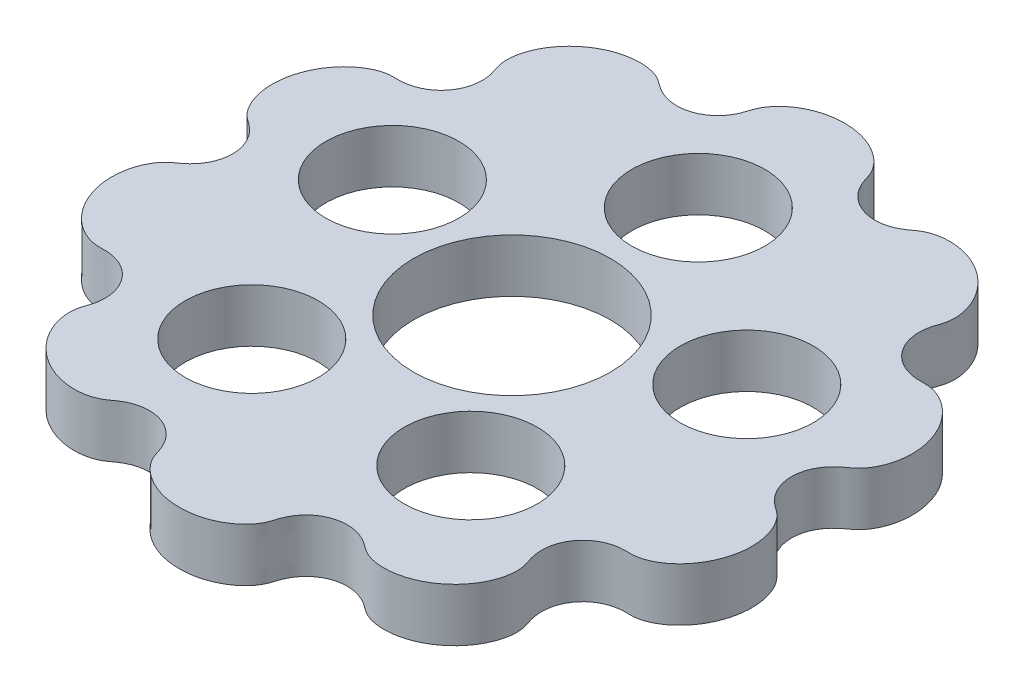
SolidWorks part; units mm, degrees
ref_plane "Front Plane" through (0, 0, 0) normal (0, 0, 1) x (1, 0, 0)
ref_plane "Top Plane" through (0, 0, 0) normal (0, 1, 0) x (1, 0, 0)
ref_plane "Right Plane" through (0, 0, 0) normal (1, 0, 0) x (0, 0, -1)
sketch "Sketch1" plane through (0, 0, 0) normal (0, 1, 0) x (1, 0, 0)
  line L0 (52.5001, 0.0415) -> (52.5, 0)
  spline S0 degree 4 poles (50.5137, 27.6197) (50.9839, 27.5812) (51.8522, 27.4156) (53.4265, 26.845) (55.5206, 25.4783) (57.5342, 23.3814) (59.2047, 20.4519) (60.0271, 17.5454) (60.2034, 14.9243) (59.9788, 12.88) (59.6275, 11.4276) (59.1883, 10.2668) (58.7445, 9.3842) (58.2852, 8.6575) (57.8967, 8.1479) (57.5285, 7.7404) (57.208, 7.4353) (56.9519, 7.2176) (56.636, 6.976) (56.3222, 6.7567) (56.0097, 6.5358) (55.6427, 6.2595) (55.2623, 5.9506) (54.8217, 5.547) (54.3431, 5.0304) (53.8948, 4.4489) (53.5024, 3.829) (53.1698, 3.1757) (52.9427, 2.6012) (52.7935, 2.1219) (52.6991, 1.7471) (52.6422, 1.4822) (52.5946, 1.2148) (52.5565, 0.9474) (52.5279, 0.6739) (52.5088, 0.4201) (52.4999, 0.1167) (52.4991, -0.0504) (52.5043, -0.2752) (52.5136, -0.4749) (52.531, -0.7089) (52.5611, -0.9887) (52.6094, -1.3156) (52.6824, -1.6816) (52.7948, -2.1324) (53.0174, -2.8309) (53.4278, -3.7531) (54.0707, -4.7446) (54.8301, -5.5754) (55.5037, -6.157) (56.0124, -6.539) (56.4108, -6.818) (56.7924, -7.0894) (57.142, -7.3728) (57.5207, -7.7299) (57.9157, -8.1698) (58.4933, -8.9376) (59.0883, -9.9991) (59.6003, -11.3023) (60.0493, -13.197) (60.2144, -15.3932) (59.9369, -17.9726) (59.1239, -20.4456) (58.0615, -22.4161) (56.9372, -23.9185) (55.905, -25.0086) (54.6695, -26.0286) (53.2974, -26.8599) (52.0381, -27.3608) (50.9617, -27.59) (50.2174, -27.6452) (49.7229, -27.6436) (49.2436, -27.6335) (48.779, -27.6384) (48.2213, -27.6667) (47.4128, -27.7584) (46.3618, -27.9976) (45.1066, -28.5075) (43.8309, -29.342) (42.7421, -30.4104) (41.8865, -31.6717) (41.3014, -33.0572) (40.9958, -34.5041) (40.9663, -35.8518) (41.1191, -36.9419) (41.3328, -37.7752) (41.5169, -38.3484) (41.6666, -38.779) (41.8007, -39.1927) (41.9033, -39.5936) (41.9931, -40.0789) (42.0522, -40.6496) (42.0653, -41.3702) (41.996, -42.235) (41.8118, -43.2683) (41.4633, -44.4497) (40.7951, -46.0262) (39.6316, -47.8911) (37.8812, -49.8104) (35.7571, -51.3288) (33.7228, -52.2936) (31.9095, -52.8411) (30.4175, -53.1066) (28.8666, -53.1869) (27.5064, -53.0662) (26.3596, -52.8062) (25.4812, -52.4838) (24.9495, -52.2275) (24.5453, -51.9879) (24.1978, -51.7525) (23.9172, -51.5436) (23.6381, -51.3332) (23.232, -51.041) (22.7473, -50.7202) (21.9663, -50.2822) (20.8507, -49.8374) (19.5115, -49.545) (17.9731, -49.5159) (16.4648, -49.7896) (15.0488, -50.3537) (13.7947, -51.1659) (12.7367, -52.1794) (11.9586, -53.2621) (11.4706, -54.2355) (11.1728, -55.0336) (10.9942, -55.6012) (10.863, -56.033) (10.7199, -56.4397) (10.5576, -56.817) (10.3352, -57.2528) (10.0392, -57.7376) (9.6188, -58.3143) (9.0494, -58.9575) (8.026, -59.9148) (6.4149, -61.014) (4.1854, -61.9905) (1.3392, -62.5603) (-1.5555, -62.5373) (-4.0271, -62.0021) (-6.0205, -61.178) (-7.4336, -60.3182) (-8.3498, -59.6134) (-9.0591, -58.943) (-9.5889, -58.3483) (-10.0398, -57.7416) (-10.3653, -57.2066) (-10.602, -56.7252) (-10.7847, -56.2661) (-10.9036, -55.901) (-11.0089, -55.5537) (-11.134, -55.1628) (-11.2692, -54.775) (-11.524, -54.1353) (-11.9704, -53.2592) (-12.6641, -52.2657) (-13.6882, -51.2531) (-14.8984, -50.4381) (-16.2819, -49.8468) (-17.79, -49.53) (-19.3539, -49.5225) (-20.902, -49.8356) (-22.1148, -50.342) (-22.9585, -50.8486) (-23.5039, -51.2352) (-23.8505, -51.4923) (-24.1373, -51.7091) (-24.4322, -51.9153) (-24.8449, -52.1675) (-25.3219, -52.4127) (-25.9648, -52.6717) (-26.7816, -52.9052) (-27.8082, -53.0938) (-29.0445, -53.179) (-30.4446, -53.106) (-31.9828, -52.8257) (-33.8493, -52.2469) (-35.9581, -51.2161) (-37.8451, -49.8114) (-39.4342, -48.0894) (-40.5175, -46.4752) (-41.2219, -45.0883) (-41.6768, -43.8047) (-41.9333, -42.6668) (-42.0454, -41.7024) (-42.0674, -40.926) (-42.0211, -40.2648) (-41.9322, -39.7238) (-41.8104, -39.2249) (-41.689, -38.8442) (-41.5576, -38.4672) (-41.4084, -38.0119) (-41.2638, -37.5172) (-41.1226, -36.9013) (-41.0183, -36.1616) (-40.9838, -35.3806) (-41.0358, -34.4173) (-41.2507, -33.2654) (-41.725, -31.9746) (-42.561, -30.6268) (-43.6662, -29.4706) (-44.9678, -28.5757) (-46.4068, -27.9666) (-47.6784, -27.6986) (-48.7214, -27.6297) (-49.4554, -27.6377) (-49.8839, -27.6454) (-50.3123, -27.6377) (-50.9842, -27.5865) (-52.0202, -27.3671) (-53.2997, -26.8583) (-54.684, -26.0188) (-55.9292, -24.9892) (-56.989, -23.8601) (-58.1366, -22.3017) (-59.199, -20.2738) (-59.9869, -17.7487) (-60.2196, -15.1335) (-60.0091, -12.9319) (-59.532, -11.1058) (-59.0205, -9.8698) (-58.4445, -8.8705) (-57.9119, -8.1659) (-57.5339, -7.7452) (-57.186, -7.4139) (-56.8826, -7.1604) (-56.5405, -6.9081) (-56.167, -6.6487) (-55.6705, -6.2883) (-54.9929, -5.7308) (-54.2103, -4.9216) (-53.4318, -3.7935) (-52.83, -2.4288) (-52.5002, -0.9669) (-52.4571, 0.5522) (-52.7153, 2.061) (-53.2627, 3.4832) (-54.0035, 4.6556) (-54.7388, 5.4802) (-55.3636, 6.0389) (-55.8227, 6.3989) (-56.1997, 6.6716) (-56.5809, 6.9362) (-56.9524, 7.213) (-57.357, 7.5655) (-57.779, 8.0056) (-58.333, 8.7033) (-58.9309, 9.69) (-59.4684, 10.9205) (-59.881, 12.3939) (-60.1041, 13.8869) (-60.1629, 15.7726) (-59.8944, 18.0319) (-59.2221, 20.2152) (-58.1717, 22.2394) (-57.0556, 23.7771) (-56.0256, 24.8955) (-54.8008, 25.934) (-53.5992, 26.6866) (-52.4791, 27.1881) (-51.5414, 27.4638) (-50.908, 27.5862) (-50.3231, 27.6424) (-49.7934, 27.6455) (-49.1614, 27.6309) (-48.4256, 27.6439) (-47.4521, 27.7432) (-46.2534, 28.0311) (-44.967, 28.579) (-43.6819, 29.4595) (-42.5816, 30.6012) (-41.7415, 31.9406) (-41.2602, 33.2313) (-41.0399, 34.3848) (-40.9839, 35.3498) (-41.0156, 36.1324) (-41.1174, 36.8734) (-41.2569, 37.4904) (-41.4004, 37.9861) (-41.549, 38.442) (-41.6805, 38.8194) (-41.8032, 39.2) (-41.9273, 39.699) (-42.0184, 40.2402) (-42.0669, 40.9021) (-42.0471, 41.6796) (-41.9591, 42.4524) (-41.8098, 43.2156) (-41.553, 44.1531) (-41.1412, 45.2456) (-40.5256, 46.4617) (-39.4424, 48.0795) (-37.854, 49.8036) (-35.9683, 51.2097) (-33.8615, 52.2416) (-31.9987, 52.8217) (-30.4634, 53.1036) (-28.8372, 53.1913) (-27.4076, 53.0564) (-26.2012, 52.7644) (-25.2794, 52.3967) (-24.6778, 52.0804) (-24.2175, 51.7696) (-23.874, 51.5099) (-23.5282, 51.253) (-22.9846, 50.8655) (-22.1441, 50.3567) (-20.9354, 49.8462) (-19.3913, 49.5265) (-17.8293, 49.5261) (-16.3197, 49.835) (-14.9321, 50.4197) (-13.7159, 51.2302) (-12.6861, 52.2396) (-11.9875, 53.2313) (-11.5372, 54.1066) (-11.2802, 54.7459) (-11.1435, 55.1346) (-11.0173, 55.5266) (-10.9116, 55.8747) (-10.7936, 56.2409) (-10.6126, 56.7015) (-10.3777, 57.1843) (-10.0537, 57.7211) (-9.604, 58.33) (-9.0747, 58.927) (-8.3659, 59.5999) (-7.4495, 60.3076) (-6.0356, 61.1707) (-4.0402, 61.9984) (-1.5791, 62.5336) (1.2918, 62.5618) (3.7523, 62.0799) (5.746, 61.3079) (7.1998, 60.4742) (8.1838, 59.7553) (9.0853, 58.9347) (9.773, 58.1413) (10.2664, 57.4013) (10.5906, 56.7517) (10.783, 56.2729) (10.9298, 55.8188) (11.0821, 55.3106) (11.2729, 54.758) (11.5071, 54.1882) (11.7952, 53.6084) (12.2337, 52.8793) (12.8842, 52.0381) (13.7961, 51.1677) (15.0329, 50.3633) (16.4413, 49.7961) (17.9467, 49.5176) (19.4906, 49.5425) (20.9881, 49.8658) (22.167, 50.3685) (23.0025, 50.8774) (23.5419, 51.263) (23.8838, 51.5174) (24.2239, 51.7741) (24.6778, 52.0798) (25.2689, 52.3913) (26.1721, 52.7541) (27.3524, 53.0458) (28.7524, 53.1873) (30.3468, 53.1154) (31.8542, 52.855) (33.6865, 52.3092) (35.7348, 51.3434) (37.8679, 49.8229) (39.6227, 47.9021) (40.7867, 46.0415) (41.4564, 44.4684) (41.8066, 43.2894) (41.9928, 42.2582) (42.0643, 41.3949) (42.0536, 40.6755) (41.9967, 40.1055) (41.9092, 39.6204) (41.8084, 39.2195) (41.676, 38.8059) (41.5263, 38.3761) (41.3414, 37.8045) (41.1252, 36.9734) (40.9684, 35.8858) (40.9919, 34.5404) (41.2901, 33.0941) (41.8697, 31.7015) (42.7272, 30.4257) (43.8268, 29.3427) (45.1246, 28.4959) (46.3067, 28.0217) (47.2768, 27.7899) (48.0092, 27.6897) (48.4792, 27.6507) (48.9504, 27.6345) (49.4215, 27.6363) (49.8923, 27.6467) (50.3633, 27.638) (50.9053, 27.5853) (51.5125, 27.4703) (52.3773, 27.2213) (53.4476, 26.7608) (54.6115, 26.0642) (56.1125, 24.854) (57.6371, 23.1341) (58.9891, 20.8488) (59.9328, 17.9964) (60.2137, 15.4073) (60.0515, 13.2142) (59.6063, 11.3218) (59.0976, 10.0195) (58.506, 8.9581) (57.9317, 8.1896) (57.539, 7.749) (57.1625, 7.3909) (56.8149, 7.1065) (56.4347, 6.8345) (56.0365, 6.5563) (55.5274, 6.176) (54.8528, 5.5976) (54.2148, 4.9051) (53.6468, 4.092) (53.2635, 3.3667) (53.0462, 2.8643) (52.8911, 2.4331) (52.7829, 2.0805) (52.6912, 1.7204) (52.6165, 1.3555) (52.5665, 1.0291) (52.5349, 0.7496) (52.5162, 0.516) (52.5059, 0.3168) (52.4995, 0.0913) (52.4994, -0.0498) (52.5037, -0.2593) (52.5117, -0.4351) (52.5205, -0.5703) (52.5346, -0.7372) (52.5633, -1.0062) (52.6182, -1.3763) (52.7261, -1.8914) (52.9083, -2.5128) (53.1636, -3.1635) (53.5039, -3.8331) (53.9066, -4.4669) (54.3673, -5.0599) (54.8485, -5.5734) (55.3344, -6.0144) (55.8114, -6.3927) (56.2105, -6.6789) (56.5558, -6.9194) (56.8563, -7.1425) (57.1104, -7.3492) (57.439, -7.6488) (57.8233, -8.059) (58.2283, -8.5752) (58.7047, -9.312) (59.1632, -10.2073) (59.5635, -11.2492) (59.8752, -12.434) (60.1105, -13.9192) (60.1782, -15.9789) (59.8062, -18.5974) (58.6629, -21.6162) (56.9432, -24.0677) (55.1186, -25.7376) (53.5134, -26.7273) (52.3156, -27.2564) (51.3998, -27.5063) (50.8196, -27.5938) (50.5276, -27.6185) knots 0 0 0 0 0 0.003711 0.006927 0.013093 0.019514 0.026363 0.033214 0.036638 0.040062 0.042505 0.044948 0.046387 0.047827 0.049266 0.049986 0.050706 0.051309 0.051911 0.053117 0.053719 0.054322 0.055527 0.056973 0.058419 0.05986 0.0613 0.062741 0.064183 0.064716 0.06525 0.065783 0.066317 0.06685 0.067384 0.067918 0.068451 0.068823 0.069195 0.069567 0.069939 0.070683 0.071427 0.072155 0.072882 0.074337 0.077196 0.080074 0.082134 0.083164 0.084195 0.08508 0.085965 0.08685 0.087735 0.089174 0.090614 0.094403 0.097279 0.100155 0.105904 0.111655 0.117552 0.1205 0.123448 0.126397 0.129346 0.133079 0.136028 0.137001 0.137974 0.138947 0.13992 0.140776 0.141631 0.143342 0.146321 0.149231 0.152234 0.155269 0.158252 0.161152 0.164002 0.166843 0.168806 0.169787 0.170769 0.171582 0.172396 0.17321 0.174024 0.175466 0.176908 0.178876 0.180844 0.183715 0.186585 0.192323 0.198063 0.204015 0.206991 0.209967 0.212943 0.215919 0.219183 0.220677 0.222171 0.223273 0.223823 0.224374 0.225475 0.226025 0.226576 0.228312 0.230048 0.233064 0.235996 0.239038 0.242085 0.245052 0.247918 0.250729 0.253554 0.255493 0.256462 0.257431 0.258238 0.259046 0.259854 0.260662 0.262088 0.263514 0.265465 0.267416 0.273101 0.278785 0.28447 0.290104 0.295736 0.298553 0.30137 0.303095 0.30482 0.306227 0.307634 0.309039 0.309742 0.310445 0.311522 0.312061 0.312599 0.313677 0.314754 0.317479 0.320324 0.323167 0.326029 0.328899 0.332099 0.335219 0.338253 0.341251 0.342384 0.34295 0.343516 0.344649 0.345215 0.345781 0.347323 0.348865 0.350662 0.352459 0.355528 0.358598 0.361668 0.364738 0.370878 0.376986 0.38004 0.383094 0.386148 0.389202 0.390729 0.392257 0.393783 0.395309 0.395938 0.396567 0.397824 0.398453 0.399082 0.400339 0.401881 0.403423 0.404954 0.406485 0.409464 0.412615 0.415708 0.418884 0.421967 0.424963 0.427932 0.429056 0.43018 0.430743 0.431305 0.432429 0.43548 0.439041 0.442082 0.445123 0.448164 0.451204 0.457286 0.46306 0.468832 0.47172 0.474607 0.47788 0.479326 0.480773 0.48155 0.482328 0.483106 0.483883 0.484896 0.485909 0.487935 0.490785 0.493727 0.496638 0.499606 0.502511 0.505617 0.508611 0.511524 0.513364 0.514284 0.515204 0.516115 0.517026 0.517938 0.518849 0.520335 0.521821 0.52494 0.527905 0.530869 0.533833 0.536797 0.542726 0.548698 0.551683 0.554667 0.557654 0.56064 0.564291 0.565785 0.56728 0.568321 0.569363 0.570405 0.571447 0.5733 0.575153 0.578095 0.581117 0.58424 0.587334 0.590492 0.593476 0.595011 0.596546 0.59809 0.599633 0.600892 0.601521 0.602151 0.603409 0.604039 0.604668 0.606196 0.607725 0.609254 0.610783 0.612313 0.613842 0.6169 0.619959 0.623017 0.629134 0.635265 0.63833 0.641395 0.644459 0.647524 0.651113 0.652653 0.654193 0.655323 0.656453 0.657019 0.657584 0.658714 0.661709 0.664737 0.667852 0.671048 0.673919 0.676788 0.679636 0.682487 0.685207 0.686288 0.687369 0.687909 0.68845 0.68953 0.690234 0.690937 0.692343 0.693753 0.695162 0.696889 0.698617 0.701438 0.70426 0.7099 0.715542 0.721126 0.72671 0.729502 0.732295 0.73429 0.736286 0.739084 0.740539 0.741266 0.741994 0.743144 0.744294 0.745444 0.746594 0.74799 0.749386 0.752135 0.754942 0.757861 0.760934 0.764011 0.766914 0.769939 0.772922 0.774041 0.7746 0.775159 0.776277 0.777396 0.778902 0.780409 0.783927 0.786931 0.789935 0.792938 0.795942 0.801949 0.80768 0.813409 0.816275 0.819141 0.821107 0.823072 0.824512 0.825951 0.826764 0.827577 0.82839 0.829203 0.830182 0.831161 0.833118 0.835958 0.838802 0.841696 0.844677 0.847761 0.850824 0.853764 0.856799 0.857727 0.858655 0.859582 0.86051 0.861437 0.862364 0.86329 0.864217 0.86572 0.867222 0.870363 0.873362 0.876361 0.882358 0.888357 0.894099 0.89984 0.902711 0.905583 0.909366 0.910804 0.912242 0.913125 0.914008 0.914891 0.915774 0.916804 0.917834 0.919893 0.922762 0.924189 0.925616 0.926343 0.927069 0.927795 0.928521 0.929264 0.930008 0.930379 0.930751 0.931123 0.931494 0.932028 0.932295 0.932562 0.932829 0.933096 0.93363 0.934697 0.935765 0.937242 0.938718 0.940194 0.941669 0.943146 0.944622 0.945727 0.946831 0.947936 0.948488 0.949041 0.949777 0.950514 0.951987 0.953461 0.954935 0.957413 0.959892 0.962228 0.964563 0.969234 0.976064 0.982895 0.989723 0.992556 0.995389 0.997695 1 1 1 1 1 construction
  spline S1 degree 4 poles (52.5, 0) (52.5, -0.0408) (52.5008, -0.1231) (52.5043, -0.2752) (52.5136, -0.4749) (52.531, -0.7089) (52.5611, -0.9887) (52.6094, -1.3156) (52.6824, -1.6816) (52.7948, -2.1324) (53.0174, -2.8309) (53.4278, -3.7531) (54.0707, -4.7446) (54.8301, -5.5754) (55.5037, -6.157) (56.0124, -6.539) (56.4108, -6.818) (56.7924, -7.0894) (57.142, -7.3728) (57.5207, -7.7299) (57.9157, -8.1698) (58.4933, -8.9376) (59.0883, -9.9991) (59.6003, -11.3023) (60.0493, -13.197) (60.2144, -15.3932) (59.9369, -17.9726) (59.1239, -20.4456) (58.0615, -22.4161) (56.9372, -23.9185) (55.905, -25.0086) (54.6695, -26.0286) (53.2974, -26.8599) (52.0381, -27.3608) (50.9617, -27.59) (50.2174, -27.6452) (49.7229, -27.6436) (49.2436, -27.6335) (48.779, -27.6384) (48.2213, -27.6667) (47.4128, -27.7584) (46.3618, -27.9976) (45.1066, -28.5075) (43.8309, -29.342) (42.7421, -30.4104) (41.8865, -31.6717) (41.3014, -33.0572) (40.9958, -34.5041) (40.9663, -35.8518) (41.1191, -36.9419) (41.3328, -37.7752) (41.5169, -38.3484) (41.6666, -38.779) (41.8007, -39.1927) (41.9033, -39.5936) (41.9931, -40.0789) (42.0522, -40.6496) (42.0653, -41.3702) (41.996, -42.235) (41.8118, -43.2683) (41.4633, -44.4497) (40.7951, -46.0262) (39.6316, -47.8911) (37.8812, -49.8104) (35.7571, -51.3288) (33.7228, -52.2936) (31.9095, -52.8411) (30.4175, -53.1066) (28.8666, -53.1869) (27.5064, -53.0662) (26.3596, -52.8062) (25.4812, -52.4838) (24.9495, -52.2275) (24.5453, -51.9879) (24.1978, -51.7525) (23.9172, -51.5436) (23.6381, -51.3332) (23.232, -51.041) (22.7473, -50.7202) (21.9663, -50.2822) (20.8507, -49.8374) (19.5115, -49.545) (17.9731, -49.5159) (16.4648, -49.7896) (15.0488, -50.3537) (13.7947, -51.1659) (12.7367, -52.1794) (11.9586, -53.2621) (11.4706, -54.2355) (11.1728, -55.0336) (10.9942, -55.6012) (10.863, -56.033) (10.7199, -56.4397) (10.5576, -56.817) (10.3352, -57.2528) (10.0392, -57.7376) (9.6188, -58.3143) (9.0494, -58.9575) (8.026, -59.9148) (6.4149, -61.014) (4.1854, -61.9905) (1.3392, -62.5603) (-1.5555, -62.5373) (-4.0271, -62.0021) (-6.0205, -61.178) (-7.4336, -60.3182) (-8.3498, -59.6134) (-9.0591, -58.943) (-9.5889, -58.3483) (-10.0398, -57.7416) (-10.3653, -57.2066) (-10.602, -56.7252) (-10.7847, -56.2661) (-10.9036, -55.901) (-11.0089, -55.5537) (-11.134, -55.1628) (-11.2692, -54.775) (-11.524, -54.1353) (-11.9704, -53.2592) (-12.6641, -52.2657) (-13.6882, -51.2531) (-14.8984, -50.4381) (-16.2819, -49.8468) (-17.79, -49.53) (-19.3539, -49.5225) (-20.902, -49.8356) (-22.1148, -50.342) (-22.9585, -50.8486) (-23.5039, -51.2352) (-23.8505, -51.4923) (-24.1373, -51.7091) (-24.4322, -51.9153) (-24.8449, -52.1675) (-25.3219, -52.4127) (-25.9648, -52.6717) (-26.7816, -52.9052) (-27.8082, -53.0938) (-29.0445, -53.179) (-30.4446, -53.106) (-31.9828, -52.8257) (-33.8493, -52.2469) (-35.9581, -51.2161) (-37.8451, -49.8114) (-39.4342, -48.0894) (-40.5175, -46.4752) (-41.2219, -45.0883) (-41.6768, -43.8047) (-41.9333, -42.6668) (-42.0454, -41.7024) (-42.0674, -40.926) (-42.0211, -40.2648) (-41.9322, -39.7238) (-41.8104, -39.2249) (-41.689, -38.8442) (-41.5576, -38.4672) (-41.4084, -38.0119) (-41.2638, -37.5172) (-41.1226, -36.9013) (-41.0183, -36.1616) (-40.9838, -35.3806) (-41.0358, -34.4173) (-41.2507, -33.2654) (-41.725, -31.9746) (-42.561, -30.6268) (-43.6662, -29.4706) (-44.9678, -28.5757) (-46.4068, -27.9666) (-47.6784, -27.6986) (-48.7214, -27.6297) (-49.4554, -27.6377) (-49.8839, -27.6454) (-50.3123, -27.6377) (-50.9842, -27.5865) (-52.0202, -27.3671) (-53.2997, -26.8583) (-54.684, -26.0188) (-55.9292, -24.9892) (-56.989, -23.8601) (-58.1366, -22.3017) (-59.199, -20.2738) (-59.9869, -17.7487) (-60.2196, -15.1335) (-60.0091, -12.9319) (-59.532, -11.1058) (-59.0205, -9.8698) (-58.4445, -8.8705) (-57.9119, -8.1659) (-57.5339, -7.7452) (-57.186, -7.4139) (-56.8826, -7.1604) (-56.5405, -6.9081) (-56.167, -6.6487) (-55.6705, -6.2883) (-54.9929, -5.7308) (-54.2103, -4.9216) (-53.4318, -3.7935) (-52.83, -2.4288) (-52.5002, -0.9669) (-52.4571, 0.5522) (-52.7153, 2.061) (-53.2627, 3.4832) (-54.0035, 4.6556) (-54.7388, 5.4802) (-55.3636, 6.0389) (-55.8227, 6.3989) (-56.1997, 6.6716) (-56.5809, 6.9362) (-56.9524, 7.213) (-57.357, 7.5655) (-57.779, 8.0056) (-58.333, 8.7033) (-58.9309, 9.69) (-59.4684, 10.9205) (-59.881, 12.3939) (-60.1041, 13.8869) (-60.1629, 15.7726) (-59.8944, 18.0319) (-59.2221, 20.2152) (-58.1717, 22.2394) (-57.0556, 23.7771) (-56.0256, 24.8955) (-54.8008, 25.934) (-53.5992, 26.6866) (-52.4791, 27.1881) (-51.5414, 27.4638) (-50.908, 27.5862) (-50.3231, 27.6424) (-49.7934, 27.6455) (-49.1614, 27.6309) (-48.4256, 27.6439) (-47.4521, 27.7432) (-46.2534, 28.0311) (-44.967, 28.579) (-43.6819, 29.4595) (-42.5816, 30.6012) (-41.7415, 31.9406) (-41.2602, 33.2313) (-41.0399, 34.3848) (-40.9839, 35.3498) (-41.0156, 36.1324) (-41.1174, 36.8734) (-41.2569, 37.4904) (-41.4004, 37.9861) (-41.549, 38.442) (-41.6805, 38.8194) (-41.8032, 39.2) (-41.9273, 39.699) (-42.0184, 40.2402) (-42.0669, 40.9021) (-42.0471, 41.6796) (-41.9591, 42.4524) (-41.8098, 43.2156) (-41.553, 44.1531) (-41.1412, 45.2456) (-40.5256, 46.4617) (-39.4424, 48.0795) (-37.854, 49.8036) (-35.9683, 51.2097) (-33.8615, 52.2416) (-31.9987, 52.8217) (-30.4634, 53.1036) (-28.8372, 53.1913) (-27.4076, 53.0564) (-26.2012, 52.7644) (-25.2794, 52.3967) (-24.6778, 52.0804) (-24.2175, 51.7696) (-23.874, 51.5099) (-23.5282, 51.253) (-22.9846, 50.8655) (-22.1441, 50.3567) (-20.9354, 49.8462) (-19.3913, 49.5265) (-17.8293, 49.5261) (-16.3197, 49.835) (-14.9321, 50.4197) (-13.7159, 51.2302) (-12.6861, 52.2396) (-11.9875, 53.2313) (-11.5372, 54.1066) (-11.2802, 54.7459) (-11.1435, 55.1346) (-11.0173, 55.5266) (-10.9116, 55.8747) (-10.7936, 56.2409) (-10.6126, 56.7015) (-10.3777, 57.1843) (-10.0537, 57.7211) (-9.604, 58.33) (-9.0747, 58.927) (-8.3659, 59.5999) (-7.4495, 60.3076) (-6.0356, 61.1707) (-4.0402, 61.9984) (-1.5791, 62.5336) (1.2918, 62.5618) (3.7523, 62.0799) (5.746, 61.3079) (7.1998, 60.4742) (8.1838, 59.7553) (9.0853, 58.9347) (9.773, 58.1413) (10.2664, 57.4013) (10.5906, 56.7517) (10.783, 56.2729) (10.9298, 55.8188) (11.0821, 55.3106) (11.2729, 54.758) (11.5071, 54.1882) (11.7952, 53.6084) (12.2337, 52.8793) (12.8842, 52.0381) (13.7961, 51.1677) (15.0329, 50.3633) (16.4413, 49.7961) (17.9467, 49.5176) (19.4906, 49.5425) (20.9881, 49.8658) (22.167, 50.3685) (23.0025, 50.8774) (23.5419, 51.263) (23.8838, 51.5174) (24.2239, 51.7741) (24.6778, 52.0798) (25.2689, 52.3913) (26.1721, 52.7541) (27.3524, 53.0458) (28.7524, 53.1873) (30.3468, 53.1154) (31.8542, 52.855) (33.6865, 52.3092) (35.7348, 51.3434) (37.8679, 49.8229) (39.6227, 47.9021) (40.7867, 46.0415) (41.4564, 44.4684) (41.8066, 43.2894) (41.9928, 42.2582) (42.0643, 41.3949) (42.0536, 40.6755) (41.9967, 40.1055) (41.9092, 39.6204) (41.8084, 39.2195) (41.676, 38.8059) (41.5263, 38.3761) (41.3414, 37.8045) (41.1252, 36.9734) (40.9684, 35.8858) (40.9919, 34.5404) (41.2901, 33.0941) (41.8697, 31.7015) (42.7272, 30.4257) (43.8268, 29.3427) (45.1246, 28.4959) (46.3067, 28.0217) (47.2768, 27.7899) (48.0092, 27.6897) (48.4792, 27.6507) (48.9504, 27.6345) (49.4215, 27.6363) (49.8923, 27.6467) (50.3633, 27.638) (50.9053, 27.5853) (51.5125, 27.4703) (52.3773, 27.2213) (53.4476, 26.7608) (54.6115, 26.0642) (56.1125, 24.854) (57.6371, 23.1341) (58.9891, 20.8488) (59.9328, 17.9964) (60.2137, 15.4073) (60.0515, 13.2142) (59.6063, 11.3218) (59.0976, 10.0195) (58.506, 8.9581) (57.9317, 8.1896) (57.539, 7.749) (57.1625, 7.3909) (56.8149, 7.1065) (56.4347, 6.8345) (56.0365, 6.5563) (55.5274, 6.176) (54.8528, 5.5976) (54.2148, 4.9051) (53.6468, 4.092) (53.2635, 3.3667) (53.0462, 2.8643) (52.8911, 2.4331) (52.7829, 2.0805) (52.6912, 1.7204) (52.6165, 1.3555) (52.5665, 1.0291) (52.5349, 0.7496) (52.5162, 0.516) (52.5059, 0.3168) (52.5015, 0.1643) (52.5003, 0.0822) (52.5001, 0.0415) knots 0.068451 0.068451 0.068451 0.068451 0.068451 0.068823 0.069195 0.069567 0.069939 0.070683 0.071427 0.072155 0.072882 0.074337 0.077196 0.080074 0.082134 0.083164 0.084195 0.08508 0.085965 0.08685 0.087735 0.089174 0.090614 0.094403 0.097279 0.100155 0.105904 0.111655 0.117552 0.1205 0.123448 0.126397 0.129346 0.133079 0.136028 0.137001 0.137974 0.138947 0.13992 0.140776 0.141631 0.143342 0.146321 0.149231 0.152234 0.155269 0.158252 0.161152 0.164002 0.166843 0.168806 0.169787 0.170769 0.171582 0.172396 0.17321 0.174024 0.175466 0.176908 0.178876 0.180844 0.183715 0.186585 0.192323 0.198063 0.204015 0.206991 0.209967 0.212943 0.215919 0.219183 0.220677 0.222171 0.223273 0.223823 0.224374 0.225475 0.226025 0.226576 0.228312 0.230048 0.233064 0.235996 0.239038 0.242085 0.245052 0.247918 0.250729 0.253554 0.255493 0.256462 0.257431 0.258238 0.259046 0.259854 0.260662 0.262088 0.263514 0.265465 0.267416 0.273101 0.278785 0.28447 0.290104 0.295736 0.298553 0.30137 0.303095 0.30482 0.306227 0.307634 0.309039 0.309742 0.310445 0.311522 0.312061 0.312599 0.313677 0.314754 0.317479 0.320324 0.323167 0.326029 0.328899 0.332099 0.335219 0.338253 0.341251 0.342384 0.34295 0.343516 0.344649 0.345215 0.345781 0.347323 0.348865 0.350662 0.352459 0.355528 0.358598 0.361668 0.364738 0.370878 0.376986 0.38004 0.383094 0.386148 0.389202 0.390729 0.392257 0.393783 0.395309 0.395938 0.396567 0.397824 0.398453 0.399082 0.400339 0.401881 0.403423 0.404954 0.406485 0.409464 0.412615 0.415708 0.418884 0.421967 0.424963 0.427932 0.429056 0.43018 0.430743 0.431305 0.432429 0.43548 0.439041 0.442082 0.445123 0.448164 0.451204 0.457286 0.46306 0.468832 0.47172 0.474607 0.47788 0.479326 0.480773 0.48155 0.482328 0.483106 0.483883 0.484896 0.485909 0.487935 0.490785 0.493727 0.496638 0.499606 0.502511 0.505617 0.508611 0.511524 0.513364 0.514284 0.515204 0.516115 0.517026 0.517938 0.518849 0.520335 0.521821 0.52494 0.527905 0.530869 0.533833 0.536797 0.542726 0.548698 0.551683 0.554667 0.557654 0.56064 0.564291 0.565785 0.56728 0.568321 0.569363 0.570405 0.571447 0.5733 0.575153 0.578095 0.581117 0.58424 0.587334 0.590492 0.593476 0.595011 0.596546 0.59809 0.599633 0.600892 0.601521 0.602151 0.603409 0.604039 0.604668 0.606196 0.607725 0.609254 0.610783 0.612313 0.613842 0.6169 0.619959 0.623017 0.629134 0.635265 0.63833 0.641395 0.644459 0.647524 0.651113 0.652653 0.654193 0.655323 0.656453 0.657019 0.657584 0.658714 0.661709 0.664737 0.667852 0.671048 0.673919 0.676788 0.679636 0.682487 0.685207 0.686288 0.687369 0.687909 0.68845 0.68953 0.690234 0.690937 0.692343 0.693753 0.695162 0.696889 0.698617 0.701438 0.70426 0.7099 0.715542 0.721126 0.72671 0.729502 0.732295 0.73429 0.736286 0.739084 0.740539 0.741266 0.741994 0.743144 0.744294 0.745444 0.746594 0.74799 0.749386 0.752135 0.754942 0.757861 0.760934 0.764011 0.766914 0.769939 0.772922 0.774041 0.7746 0.775159 0.776277 0.777396 0.778902 0.780409 0.783927 0.786931 0.789935 0.792938 0.795942 0.801949 0.80768 0.813409 0.816275 0.819141 0.821107 0.823072 0.824512 0.825951 0.826764 0.827577 0.82839 0.829203 0.830182 0.831161 0.833118 0.835958 0.838802 0.841696 0.844677 0.847761 0.850824 0.853764 0.856799 0.857727 0.858655 0.859582 0.86051 0.861437 0.862364 0.86329 0.864217 0.86572 0.867222 0.870363 0.873362 0.876361 0.882358 0.888357 0.894099 0.89984 0.902711 0.905583 0.909366 0.910804 0.912242 0.913125 0.914008 0.914891 0.915774 0.916804 0.917834 0.919893 0.922762 0.924189 0.925616 0.926343 0.927069 0.927795 0.928521 0.929264 0.930008 0.930379 0.930751 0.931123 0.931494 0.931494 0.931494 0.931494 0.931494
extrude "Boss-Extrude1" add sketch "Sketch1" along normal blind 10
sketch "Sketch2" plane through (0, 10, 0) normal (0, 1, 0) x (1, 0, 0)
  circle A0 centre (0, 0) radius 18.5
  dimension "D1" = 37
extrude "Cut-Extrude1" cut sketch "Sketch2" against normal blind 10
sketch "Sketch3" plane through (0, 10, 0) normal (0, 1, 0) x (1, 0, 0)
  line L0 (0, 35) -> (0, 0) construction
  circle A0 centre (0, 35) radius 12.5
  circle A1 centre (0, 0) radius 35 construction
  circle A2 centre (33.287, 10.8156) radius 12.5
  circle A3 centre (20.5725, -28.3156) radius 12.5
  circle A4 centre (-20.5725, -28.3156) radius 12.5
  circle A5 centre (-33.287, 10.8156) radius 12.5
  point P16 (0, 0)
  dimension "D1" = 70
  dimension "D2" = 25
  dimension "D3" = 5
extrude "Cut-Extrude2" cut sketch "Sketch3" against normal blind 10
